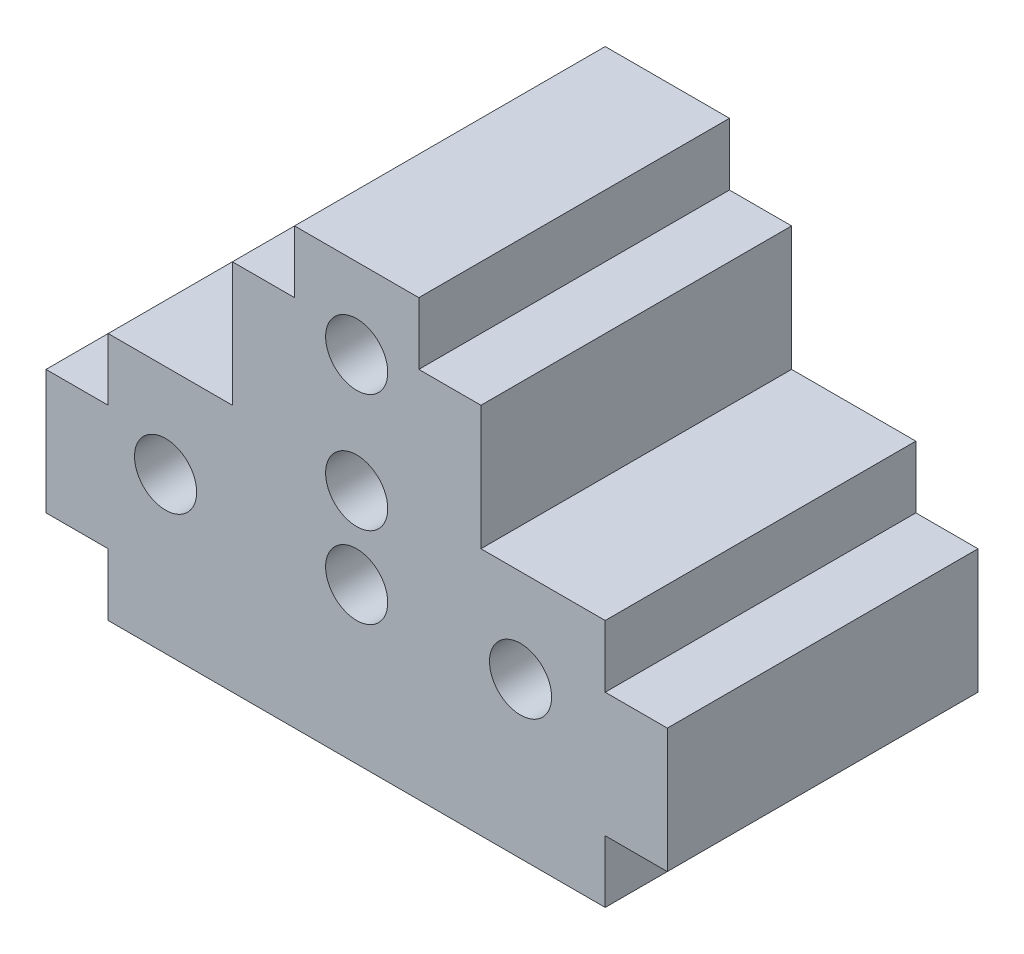
SolidWorks part; units mm, degrees
ref_plane "Front Plane" through (0, 0, 0) normal (0, 0, 1) x (1, 0, 0)
ref_plane "Top Plane" through (0, 0, 0) normal (0, 1, 0) x (1, 0, 0)
ref_plane "Right Plane" through (0, 0, 0) normal (1, 0, 0) x (0, 0, -1)
sketch "Sketch1" plane through (0, 0, 0) normal (0, 0, 1) x (1, 0, 0)
  line L0 (-10, 0) -> (10, 0) construction
  line L1 (-8, 0) -> (-8, 2)
  line L2 (-8, 2) -> (-10, 2)
  line L3 (-10, 2) -> (-10, 6)
  line L4 (-10, 6) -> (-8, 6)
  line L5 (-8, 6) -> (-8, 8)
  line L6 (-8, 8) -> (-4, 8)
  line L7 (-4, 8) -> (-4, 12)
  line L8 (-4, 12) -> (-2, 12)
  line L9 (-2, 12) -> (-2, 14)
  line L10 (-2, 14) -> (2, 14)
  line L11 (0, 15.476) -> (0, -3.0485) construction
  line L12 (2, 12) -> (2, 14)
  line L13 (4, 12) -> (2, 12)
  line L14 (4, 8) -> (4, 12)
  line L15 (8, 8) -> (4, 8)
  line L16 (8, 6) -> (8, 8)
  line L17 (10, 6) -> (8, 6)
  line L18 (10, 2) -> (10, 6)
  line L19 (8, 2) -> (10, 2)
  line L20 (8, 0) -> (8, 2)
  line L21 (-8, 0) -> (8, 0)
  point P3 (0, 0)
  point P18 (0, 14)
  dimension "D1" = 20
  dimension "D2" = 2
  dimension "D3" = 2
  dimension "D4" = 4
  dimension "D5" = 2
  dimension "D6" = 4
  dimension "D7" = 2
  dimension "D8" = 2
  dimension "D9" = 4
  dimension "D10" = 20
extrude "Boss-Extrude1" add sketch "Sketch1" along normal mid plane 10
sketch "Sketch2" plane through (0, 0, 5) normal (0, 0, 1) x (1, 0, 0)
  line L0 (-8, 0) -> (8, 0) construction
  circle A0 centre (0, 5) radius 1
  circle A1 centre (0, 7.6168) radius 1
  circle A2 centre (0, 11.4146) radius 1
  circle A3 centre (-6.1513, 5) radius 1
  circle A4 centre (5.2748, 5) radius 1
  point P10 (0, 0)
  point P14 (0, 0)
  point P15 (0, 0)
  point P16 (0, 0)
  dimension "D1" = 2
  dimension "D2" = 5
extrude "Cut-Extrude1" cut sketch "Sketch2" against normal blind 10
